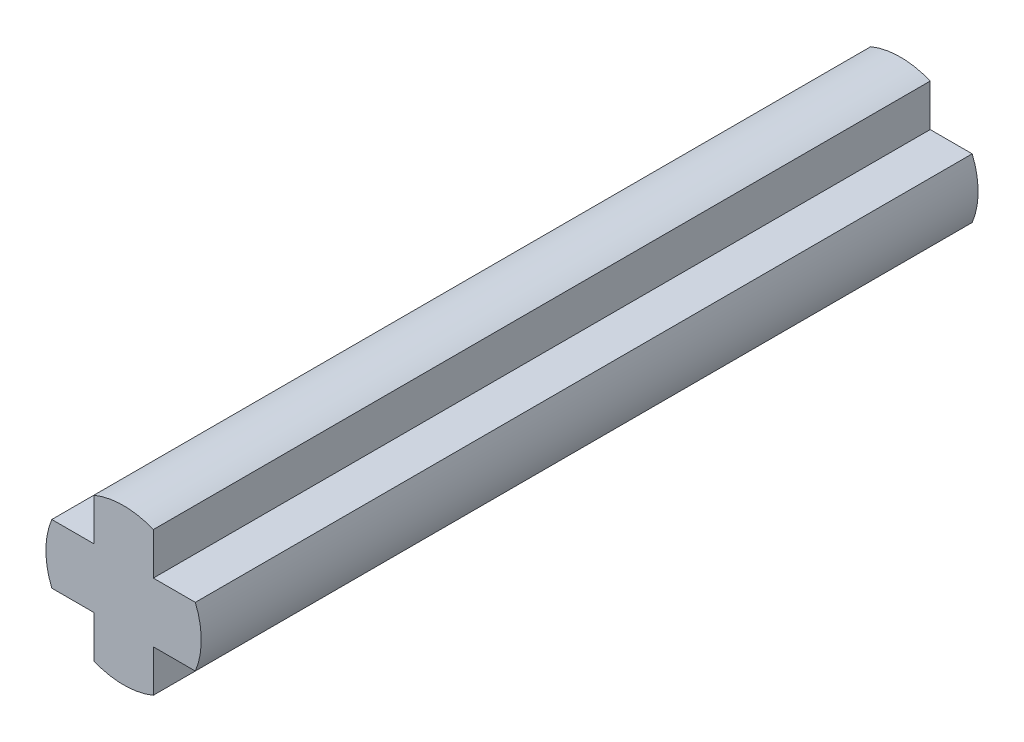
SolidWorks part; units mm, degrees
ref_plane "Front Plane" through (0, 0, 0) normal (0, 0, 1) x (1, 0, 0)
ref_plane "Top Plane" through (0, 0, 0) normal (0, 1, 0) x (1, 0, 0)
ref_plane "Right Plane" through (0, 0, 0) normal (1, 0, 0) x (0, 0, -1)
sketch "Sketch1" plane through (0, 0, 0) normal (0, 0, 1) x (1, 0, 0)
  line L0 (-0.9, 2.1708) -> (-0.9, 0.9)
  line L1 (0.9, 2.1708) -> (0.9, 0.9)
  line L2 (-2.1708, 0.9) -> (-0.9, 0.9)
  line L3 (-2.1708, -0.9) -> (-0.9, -0.9)
  line L4 (-0.9, -0.9) -> (-0.9, -2.1708)
  line L5 (0.9, 0.9) -> (2.1708, 0.9)
  line L6 (0.9, -0.9) -> (0.9, -2.1708)
  line L7 (0.9, -0.9) -> (2.1708, -0.9)
  arc A0 (-0.9, -2.1708) -> (0.9, -2.1708) centre (0, 0) ccw
  arc A1 (2.1708, -0.9) -> (2.1708, 0.9) centre (0, 0) ccw
  arc A2 (0.9, 2.1708) -> (-0.9, 2.1708) centre (0, 0) ccw
  arc A3 (-2.1708, 0.9) -> (-2.1708, -0.9) centre (0, 0) ccw
  dimension "D1" = 4.7
  dimension "D2" = 0.9
  dimension "D3" = 1.8
  dimension "D4" = 0.9
  dimension "D5" = 1.8
extrude "Boss-Extrude1" add sketch "Sketch1" along normal mid plane 23.5
